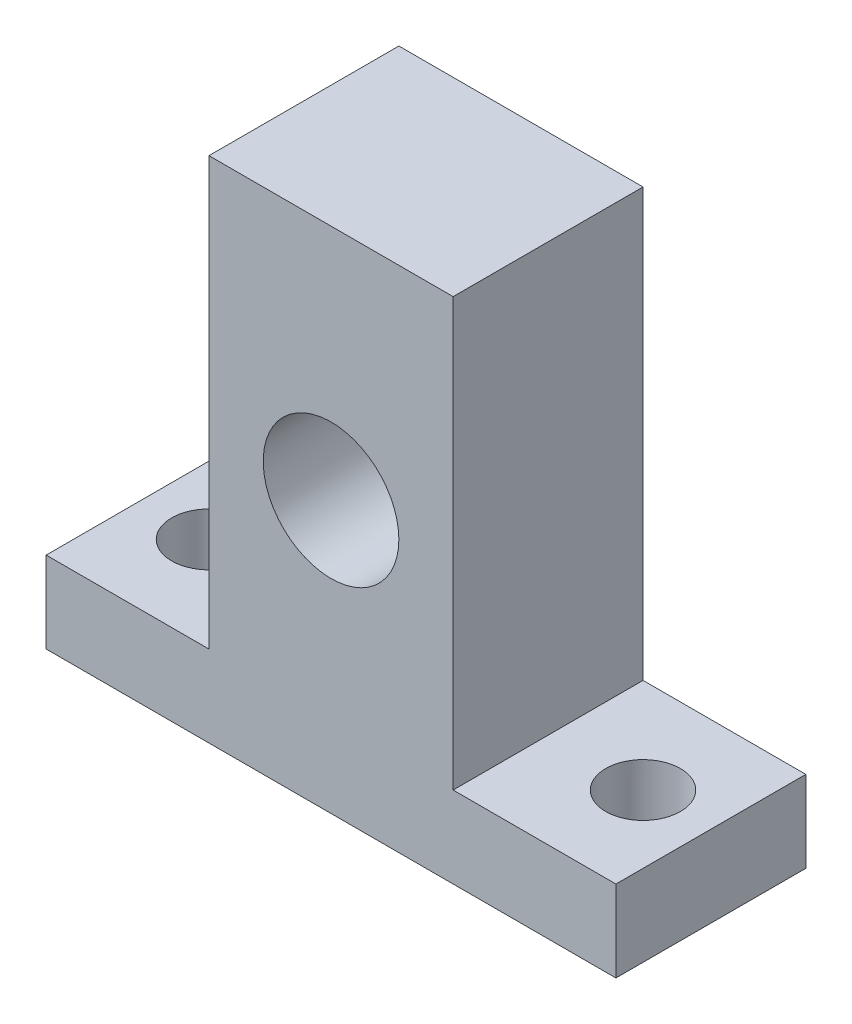
SolidWorks part; units mm, degrees
ref_plane "Front Plane" through (0, 0, 0) normal (0, 0, 1) x (1, 0, 0)
ref_plane "Top Plane" through (0, 0, 0) normal (0, 1, 0) x (1, 0, 0)
ref_plane "Right Plane" through (0, 0, 0) normal (1, 0, 0) x (0, 0, -1)
sketch "Sketch1" plane through (0, 0, 0) normal (0, 0, 1) x (1, 0, 0)
  line L0 (0, 37.5) -> (0, 0) construction
  line L1 (-9, 37.5) -> (9, 37.5)
  line L2 (-21, 0) -> (-21, 6)
  line L3 (-21, 0) -> (21, 0)
  line L4 (9, 6) -> (9, 37.5)
  line L5 (-9, 6) -> (-21, 6)
  line L6 (-9, 6) -> (-9, 37.5)
  line L7 (9, 6) -> (21, 6)
  line L8 (21, 0) -> (21, 6)
  circle A0 centre (0, 20) radius 5
  dimension "D4" = 10
  dimension "D1" = 18
  dimension "D2" = 6
  dimension "D3" = 37.5
  dimension "D5" = 42
  dimension "D6" = 20
extrude "Boss-Extrude1" add sketch "Sketch1" along normal blind 14
sketch "Sketch2" plane through (0, 0, 0) normal (0, -1, 0) x (1, 0, 0)
  line L0 (-21, 7) -> (21, 7) construction
  line L1 (-21, 14) -> (-21, 0) construction
  line L2 (21, 14) -> (21, 0) construction
  line L3 (0, 14) -> (0, 0) construction
  line L4 (-21, 14) -> (21, 14) construction
  circle A0 centre (-16, 7) radius 2.75
  circle A1 centre (16, 7) radius 2.75
  dimension "D2" = 5.5
  dimension "D1" = 32
extrude "Cut-Extrude1" cut sketch "Sketch2" against normal through all
